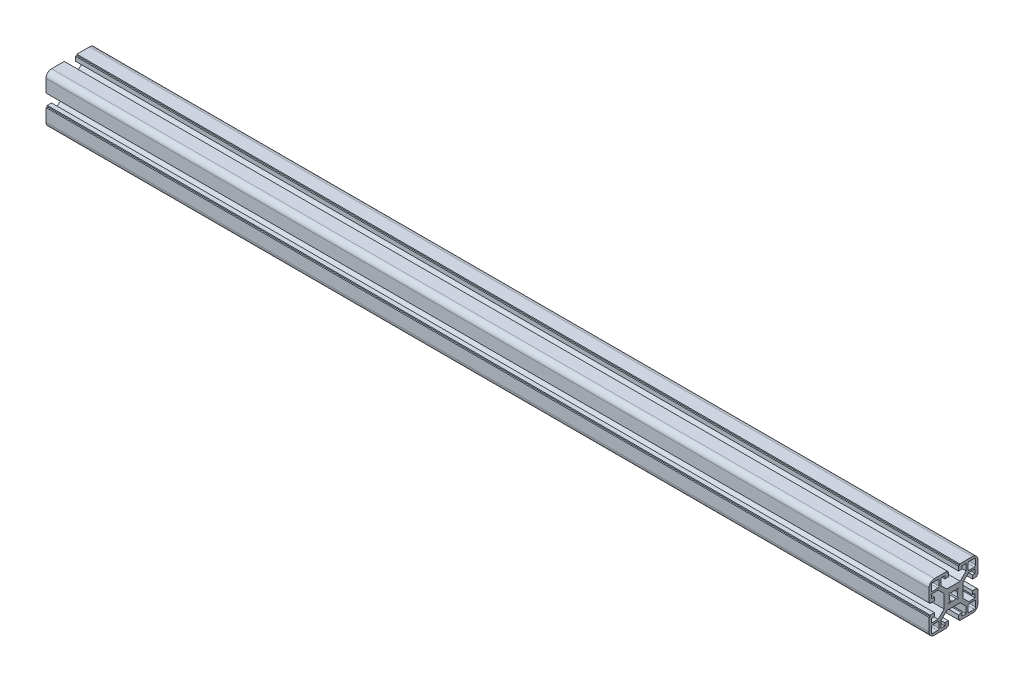
SolidWorks part; units mm, degrees
ref_plane "前视基准面" through (0, 0, 0) normal (0, 0, 1) x (1, 0, 0)
ref_plane "上视基准面" through (0, 0, 0) normal (0, 1, 0) x (1, 0, 0)
ref_plane "右视基准面" through (0, 0, 0) normal (1, 0, 0) x (0, 0, -1)
other "Configuration Table"
sketch "草图1" plane through (0, 0, 0) normal (1, 0, 0) x (0, 0, -1)
  line L0 (4.82, 19.28) -> (3.82, 19.28)
  line L1 (3.82, 19.28) -> (3.82, 15.78)
  line L2 (3.82, 15.78) -> (6.7364, 15.78)
  line L3 (6.7364, 15.78) -> (6.7364, 18.03)
  line L4 (6.7364, 18.03) -> (10.02, 18.03)
  line L5 (10.02, 18.03) -> (10.02, 12.7013)
  line L6 (10.02, 12.7013) -> (5.1987, 7.88)
  line L7 (5.1987, 7.88) -> (-5.7586, 7.88)
  line L8 (-5.7586, 7.88) -> (-10.58, 12.7013)
  line L9 (-10.58, 12.7013) -> (-10.58, 18.03)
  line L10 (-10.58, 18.03) -> (-7.2963, 18.03)
  line L11 (-7.2963, 18.03) -> (-7.2963, 15.78)
  line L12 (-7.2963, 15.78) -> (-4.38, 15.78)
  line L13 (-4.38, 15.78) -> (-4.38, 19.28)
  line L14 (-4.38, 19.28) -> (-5.38, 19.28)
  line L15 (-5.38, 19.28) -> (-5.38, 20.28)
  line L16 (-5.38, 20.28) -> (-15.78, 20.28)
  line L17 (-20.28, 15.78) -> (-20.28, 5.38)
  line L18 (-20.28, 5.38) -> (-19.28, 5.38)
  line L19 (-19.28, 5.38) -> (-19.28, 4.38)
  line L20 (-19.28, 4.38) -> (-15.78, 4.38)
  line L21 (-15.78, 4.38) -> (-15.78, 7.2963)
  line L22 (-15.78, 7.2963) -> (-18.03, 7.2963)
  line L23 (-18.03, 7.2963) -> (-18.03, 10.58)
  line L24 (-18.03, 10.58) -> (-12.7013, 10.58)
  line L25 (-12.7013, 10.58) -> (-7.88, 5.7586)
  line L26 (-7.88, 5.7586) -> (-7.88, -5.1987)
  line L27 (-7.88, -5.1987) -> (-12.7013, -10.02)
  line L28 (-12.7013, -10.02) -> (-18.03, -10.02)
  line L29 (-18.03, -10.02) -> (-18.03, -6.7364)
  line L30 (-18.03, -6.7364) -> (-15.78, -6.7364)
  line L31 (-15.78, -6.7364) -> (-15.78, -3.82)
  line L32 (-15.78, -3.82) -> (-19.28, -3.82)
  line L33 (-19.28, -3.82) -> (-19.28, -4.82)
  line L34 (-19.28, -4.82) -> (-20.28, -4.82)
  line L35 (-20.28, -4.82) -> (-20.28, -15.22)
  line L36 (-15.78, -19.72) -> (-5.38, -19.72)
  line L37 (-5.38, -19.72) -> (-5.38, -18.72)
  line L38 (-5.38, -18.72) -> (-4.38, -18.72)
  line L39 (-4.38, -18.72) -> (-4.38, -15.22)
  line L40 (-4.38, -15.22) -> (-7.2963, -15.22)
  line L41 (-7.2963, -15.22) -> (-7.2963, -17.47)
  line L42 (-7.2963, -17.47) -> (-10.58, -17.47)
  line L43 (-10.58, -17.47) -> (-10.58, -12.1414)
  line L44 (-10.58, -12.1414) -> (-5.7586, -7.32)
  line L45 (-5.7586, -7.32) -> (5.1987, -7.32)
  line L46 (5.1987, -7.32) -> (10.02, -12.1414)
  line L47 (10.02, -12.1414) -> (10.02, -17.47)
  line L48 (10.02, -17.47) -> (6.7364, -17.47)
  line L49 (6.7364, -17.47) -> (6.7364, -15.22)
  line L50 (6.7364, -15.22) -> (3.82, -15.22)
  line L51 (3.82, -15.22) -> (3.82, -18.72)
  line L52 (3.82, -18.72) -> (4.82, -18.72)
  line L53 (4.82, -18.72) -> (4.82, -19.72)
  line L54 (4.82, -19.72) -> (15.22, -19.72)
  line L55 (19.72, -15.22) -> (19.72, -4.82)
  line L56 (19.72, -4.82) -> (18.72, -4.82)
  line L57 (18.72, -4.82) -> (18.72, -3.82)
  line L58 (18.72, -3.82) -> (15.22, -3.82)
  line L59 (15.22, -3.82) -> (15.22, -6.7364)
  line L60 (15.22, -6.7364) -> (17.47, -6.7364)
  line L61 (17.47, -6.7364) -> (17.47, -10.02)
  line L62 (17.47, -10.02) -> (12.1414, -10.02)
  line L63 (12.1414, -10.02) -> (7.32, -5.1987)
  line L64 (7.32, -5.1987) -> (7.32, 5.7586)
  line L65 (7.32, 5.7586) -> (12.1414, 10.58)
  line L66 (12.1414, 10.58) -> (17.47, 10.58)
  line L67 (17.47, 10.58) -> (17.47, 7.2963)
  line L68 (17.47, 7.2963) -> (15.22, 7.2963)
  line L69 (15.22, 7.2963) -> (15.22, 4.38)
  line L70 (15.22, 4.38) -> (18.72, 4.38)
  line L71 (18.72, 4.38) -> (18.72, 5.38)
  line L72 (18.72, 5.38) -> (19.72, 5.38)
  line L73 (19.72, 5.38) -> (19.72, 15.78)
  line L74 (15.22, 20.28) -> (4.82, 20.28)
  line L75 (4.82, 20.28) -> (4.82, 19.28)
  line L76 (-13.08, -17.72) -> (-17.28, -17.72)
  line L77 (-18.28, -16.72) -> (-18.28, -12.52)
  line L78 (-17.28, -11.52) -> (-13.08, -11.52)
  line L79 (-12.08, -12.52) -> (-12.08, -16.72)
  line L80 (-17.28, 18.28) -> (-13.08, 18.28)
  line L81 (-12.08, 17.28) -> (-12.08, 13.08)
  line L82 (-13.08, 12.08) -> (-17.28, 12.08)
  line L83 (-18.28, 13.08) -> (-18.28, 17.28)
  line L84 (16.72, 12.08) -> (12.52, 12.08)
  line L85 (11.52, 13.08) -> (11.52, 17.28)
  line L86 (12.52, 18.28) -> (16.72, 18.28)
  line L87 (17.72, 17.28) -> (17.72, 13.08)
  line L88 (3.7505, -3.0434) -> (3.0434, -3.7505)
  line L89 (3.0434, -3.7505) -> (1.7445, -2.4516)
  line L90 (-2.3044, -2.4516) -> (-3.6033, -3.7505)
  line L91 (-3.6033, -3.7505) -> (-4.3104, -3.0434)
  line L92 (-4.3104, -3.0434) -> (-3.0115, -1.7445)
  line L93 (-3.0115, 2.3044) -> (-4.3104, 3.6033)
  line L94 (-4.3104, 3.6033) -> (-3.6033, 4.3104)
  line L95 (-3.6033, 4.3104) -> (-2.3044, 3.0115)
  line L96 (1.7445, 3.0115) -> (3.0434, 4.3104)
  line L97 (3.0434, 4.3104) -> (3.7505, 3.6033)
  line L98 (3.7505, 3.6033) -> (2.4516, 2.3044)
  line L99 (2.4516, -1.7445) -> (3.7505, -3.0434)
  line L100 (17.72, -12.52) -> (17.72, -16.72)
  line L101 (16.72, -17.72) -> (12.52, -17.72)
  line L102 (11.52, -16.72) -> (11.52, -12.52)
  line L103 (12.52, -11.52) -> (16.72, -11.52)
  arc A0 (-15.78, 20.28) -> (-20.28, 15.78) centre (-15.78, 15.78) ccw
  arc A1 (-20.28, -15.22) -> (-15.78, -19.72) centre (-15.78, -15.22) ccw
  arc A2 (15.22, -19.72) -> (19.72, -15.22) centre (15.22, -15.22) ccw
  arc A3 (19.72, 15.78) -> (15.22, 20.28) centre (15.22, 15.78) ccw
  arc A4 (-12.08, -16.72) -> (-13.08, -17.72) centre (-13.08, -16.72) cw
  arc A5 (-17.28, -17.72) -> (-18.28, -16.72) centre (-17.28, -16.72) cw
  arc A6 (-18.28, -12.52) -> (-17.28, -11.52) centre (-17.28, -12.52) cw
  arc A7 (-13.08, -11.52) -> (-12.08, -12.52) centre (-13.08, -12.52) cw
  arc A8 (-18.28, 17.28) -> (-17.28, 18.28) centre (-17.28, 17.28) cw
  arc A9 (-13.08, 18.28) -> (-12.08, 17.28) centre (-13.08, 17.28) cw
  arc A10 (-12.08, 13.08) -> (-13.08, 12.08) centre (-13.08, 13.08) cw
  arc A11 (-17.28, 12.08) -> (-18.28, 13.08) centre (-17.28, 13.08) cw
  arc A12 (17.72, 13.08) -> (16.72, 12.08) centre (16.72, 13.08) cw
  arc A13 (12.52, 12.08) -> (11.52, 13.08) centre (12.52, 13.08) cw
  arc A14 (11.52, 17.28) -> (12.52, 18.28) centre (12.52, 17.28) cw
  arc A15 (16.72, 18.28) -> (17.72, 17.28) centre (16.72, 17.28) cw
  arc A16 (1.7445, -2.4516) -> (-2.3044, -2.4516) centre (-0.28, 0.28) cw
  arc A17 (-3.0115, -1.7445) -> (-3.0115, 2.3044) centre (-0.28, 0.28) cw
  arc A18 (-2.3044, 3.0115) -> (1.7445, 3.0115) centre (-0.28, 0.28) cw
  arc A19 (2.4516, 2.3044) -> (2.4516, -1.7445) centre (-0.28, 0.28) cw
  arc A20 (16.72, -11.52) -> (17.72, -12.52) centre (16.72, -12.52) cw
  arc A21 (17.72, -16.72) -> (16.72, -17.72) centre (16.72, -16.72) cw
  arc A22 (12.52, -17.72) -> (11.52, -16.72) centre (12.52, -16.72) cw
  arc A23 (11.52, -12.52) -> (12.52, -11.52) centre (12.52, -12.52) cw
extrude "凸台-拉伸1" add sketch "草图1" against normal blind 50
sketch "草图2" plane through (0, 0, 0) normal (1, 0, 0) x (0, 0, -1)
  line L4 (-17.28, -17.72) -> (-13.08, -17.72)
  line L5 (-18.28, -12.52) -> (-18.28, -16.72)
  line L6 (-13.08, -11.52) -> (-17.28, -11.52)
  line L7 (-12.08, -16.72) -> (-12.08, -12.52)
  line L8 (-17.28, -17.72) -> (-13.08, -17.72)
  line L9 (-18.28, -12.52) -> (-18.28, -16.72)
  line L10 (-13.08, -11.52) -> (-17.28, -11.52)
  line L11 (-12.08, -16.72) -> (-12.08, -12.52)
  line L12 (-13.08, 18.28) -> (-17.28, 18.28)
  line L13 (-12.08, 13.08) -> (-12.08, 17.28)
  line L14 (-17.28, 12.08) -> (-13.08, 12.08)
  line L15 (-18.28, 17.28) -> (-18.28, 13.08)
  line L16 (-13.08, 18.28) -> (-17.28, 18.28)
  line L17 (-12.08, 13.08) -> (-12.08, 17.28)
  line L18 (-17.28, 12.08) -> (-13.08, 12.08)
  line L19 (-18.28, 17.28) -> (-18.28, 13.08)
  line L20 (11.52, 17.28) -> (11.52, 13.08)
  line L21 (16.72, 18.28) -> (12.52, 18.28)
  line L22 (17.72, 13.08) -> (17.72, 17.28)
  line L23 (12.52, 12.08) -> (16.72, 12.08)
  line L24 (11.52, 17.28) -> (11.52, 13.08)
  line L25 (16.72, 18.28) -> (12.52, 18.28)
  line L26 (17.72, 13.08) -> (17.72, 17.28)
  line L27 (12.52, 12.08) -> (16.72, 12.08)
  line L28 (11.52, -12.52) -> (11.52, -16.72)
  line L29 (16.72, -11.52) -> (12.52, -11.52)
  line L30 (17.72, -16.72) -> (17.72, -12.52)
  line L31 (12.52, -17.72) -> (16.72, -17.72)
  line L32 (11.52, -12.52) -> (11.52, -16.72)
  line L33 (16.72, -11.52) -> (12.52, -11.52)
  line L34 (17.72, -16.72) -> (17.72, -12.52)
  line L35 (12.52, -17.72) -> (16.72, -17.72)
  line L36 (-4.3104, 3.6033) -> (-3.0115, 2.3044)
  line L37 (-3.6033, 4.3104) -> (-4.3104, 3.6033)
  line L38 (-2.3044, 3.0115) -> (-3.6033, 4.3104)
  line L39 (3.0434, 4.3104) -> (1.7445, 3.0115)
  line L40 (3.7505, 3.6033) -> (3.0434, 4.3104)
  line L41 (2.4516, 2.3044) -> (3.7505, 3.6033)
  line L42 (3.7505, -3.0434) -> (2.4516, -1.7445)
  line L43 (3.0434, -3.7505) -> (3.7505, -3.0434)
  line L44 (1.7445, -2.4516) -> (3.0434, -3.7505)
  line L45 (-3.6033, -3.7505) -> (-2.3044, -2.4516)
  line L46 (-4.3104, -3.0434) -> (-3.6033, -3.7505)
  line L47 (-3.0115, -1.7445) -> (-4.3104, -3.0434)
  line L48 (-4.3104, 3.6033) -> (-3.0115, 2.3044)
  line L49 (-3.6033, 4.3104) -> (-4.3104, 3.6033)
  line L50 (-2.3044, 3.0115) -> (-3.6033, 4.3104)
  line L51 (3.0434, 4.3104) -> (1.7445, 3.0115)
  line L52 (3.7505, 3.6033) -> (3.0434, 4.3104)
  line L53 (2.4516, 2.3044) -> (3.7505, 3.6033)
  line L54 (3.7505, -3.0434) -> (2.4516, -1.7445)
  line L55 (3.0434, -3.7505) -> (3.7505, -3.0434)
  line L56 (1.7445, -2.4516) -> (3.0434, -3.7505)
  line L57 (-3.6033, -3.7505) -> (-2.3044, -2.4516)
  line L58 (-4.3104, -3.0434) -> (-3.6033, -3.7505)
  line L59 (-3.0115, -1.7445) -> (-4.3104, -3.0434)
  line L84 (19.72, 5.38) -> (19.72, 15.78)
  line L85 (18.72, 5.38) -> (19.72, 5.38)
  line L86 (18.72, 4.38) -> (18.72, 5.38)
  line L87 (15.22, 4.38) -> (18.72, 4.38)
  line L88 (15.22, 7.2963) -> (15.22, 4.38)
  line L89 (17.47, 7.2963) -> (15.22, 7.2963)
  line L90 (17.47, 10.58) -> (17.47, 7.2963)
  line L91 (12.1414, 10.58) -> (17.47, 10.58)
  line L92 (7.32, 5.7586) -> (12.1414, 10.58)
  line L93 (7.32, -5.1987) -> (7.32, 5.7586)
  line L94 (12.1414, -10.02) -> (7.32, -5.1987)
  line L95 (17.47, -10.02) -> (12.1414, -10.02)
  line L96 (17.47, -6.7364) -> (17.47, -10.02)
  line L97 (15.22, -6.7364) -> (17.47, -6.7364)
  line L98 (15.22, -3.82) -> (15.22, -6.7364)
  line L99 (18.72, -3.82) -> (15.22, -3.82)
  line L100 (18.72, -4.82) -> (18.72, -3.82)
  line L101 (19.72, -4.82) -> (18.72, -4.82)
  line L102 (19.72, -15.22) -> (19.72, -4.82)
  line L103 (4.82, -19.72) -> (15.22, -19.72)
  line L104 (4.82, -18.72) -> (4.82, -19.72)
  line L105 (3.82, -18.72) -> (4.82, -18.72)
  line L106 (3.82, -15.22) -> (3.82, -18.72)
  line L107 (6.7364, -15.22) -> (3.82, -15.22)
  line L108 (6.7364, -17.47) -> (6.7364, -15.22)
  line L109 (10.02, -17.47) -> (6.7364, -17.47)
  line L110 (10.02, -12.1414) -> (10.02, -17.47)
  line L111 (5.1987, -7.32) -> (10.02, -12.1414)
  line L112 (-5.7586, -7.32) -> (5.1987, -7.32)
  line L113 (-10.58, -12.1414) -> (-5.7586, -7.32)
  line L114 (-10.58, -17.47) -> (-10.58, -12.1414)
  line L115 (-7.2963, -17.47) -> (-10.58, -17.47)
  line L116 (-7.2963, -15.22) -> (-7.2963, -17.47)
  line L117 (-4.38, -15.22) -> (-7.2963, -15.22)
  line L118 (-4.38, -18.72) -> (-4.38, -15.22)
  line L119 (-5.38, -18.72) -> (-4.38, -18.72)
  line L120 (-5.38, -19.72) -> (-5.38, -18.72)
  line L121 (-15.78, -19.72) -> (-5.38, -19.72)
  line L122 (-20.28, -4.82) -> (-20.28, -15.22)
  line L123 (-19.28, -4.82) -> (-20.28, -4.82)
  line L124 (-19.28, -3.82) -> (-19.28, -4.82)
  line L125 (-15.78, -3.82) -> (-19.28, -3.82)
  line L126 (-15.78, -6.7364) -> (-15.78, -3.82)
  line L127 (-18.03, -6.7364) -> (-15.78, -6.7364)
  line L128 (-18.03, -10.02) -> (-18.03, -6.7364)
  line L129 (-12.7013, -10.02) -> (-18.03, -10.02)
  line L130 (-7.88, -5.1987) -> (-12.7013, -10.02)
  line L131 (-7.88, 5.7586) -> (-7.88, -5.1987)
  line L132 (-12.7013, 10.58) -> (-7.88, 5.7586)
  line L133 (-18.03, 10.58) -> (-12.7013, 10.58)
  line L134 (-18.03, 7.2963) -> (-18.03, 10.58)
  line L135 (-15.78, 7.2963) -> (-18.03, 7.2963)
  line L136 (-15.78, 4.38) -> (-15.78, 7.2963)
  line L137 (-19.28, 4.38) -> (-15.78, 4.38)
  line L138 (-19.28, 5.38) -> (-19.28, 4.38)
  line L139 (-20.28, 5.38) -> (-19.28, 5.38)
  line L140 (-20.28, 15.78) -> (-20.28, 5.38)
  line L141 (-5.38, 20.28) -> (-15.78, 20.28)
  line L142 (-5.38, 19.28) -> (-5.38, 20.28)
  line L143 (-4.38, 19.28) -> (-5.38, 19.28)
  line L144 (-4.38, 15.78) -> (-4.38, 19.28)
  line L145 (-7.2963, 15.78) -> (-4.38, 15.78)
  line L146 (-7.2963, 18.03) -> (-7.2963, 15.78)
  line L147 (-10.58, 18.03) -> (-7.2963, 18.03)
  line L148 (-10.58, 12.7013) -> (-10.58, 18.03)
  line L149 (-5.7586, 7.88) -> (-10.58, 12.7013)
  line L150 (5.1987, 7.88) -> (-5.7586, 7.88)
  line L151 (10.02, 12.7013) -> (5.1987, 7.88)
  line L152 (10.02, 18.03) -> (10.02, 12.7013)
  line L153 (6.7364, 18.03) -> (10.02, 18.03)
  line L154 (6.7364, 15.78) -> (6.7364, 18.03)
  line L155 (3.82, 15.78) -> (6.7364, 15.78)
  line L156 (3.82, 19.28) -> (3.82, 15.78)
  line L157 (4.82, 19.28) -> (3.82, 19.28)
  line L158 (4.82, 20.28) -> (4.82, 19.28)
  line L159 (15.22, 20.28) -> (4.82, 20.28)
  line L160 (19.72, 5.38) -> (19.72, 15.78)
  line L161 (18.72, 5.38) -> (19.72, 5.38)
  line L162 (18.72, 4.38) -> (18.72, 5.38)
  line L163 (15.22, 4.38) -> (18.72, 4.38)
  line L164 (15.22, 7.2963) -> (15.22, 4.38)
  line L165 (17.47, 7.2963) -> (15.22, 7.2963)
  line L166 (17.47, 10.58) -> (17.47, 7.2963)
  line L167 (12.1414, 10.58) -> (17.47, 10.58)
  line L168 (7.32, 5.7586) -> (12.1414, 10.58)
  line L169 (7.32, -5.1987) -> (7.32, 5.7586)
  line L170 (12.1414, -10.02) -> (7.32, -5.1987)
  line L171 (17.47, -10.02) -> (12.1414, -10.02)
  line L172 (17.47, -6.7364) -> (17.47, -10.02)
  line L173 (15.22, -6.7364) -> (17.47, -6.7364)
  line L174 (15.22, -3.82) -> (15.22, -6.7364)
  line L175 (18.72, -3.82) -> (15.22, -3.82)
  line L176 (18.72, -4.82) -> (18.72, -3.82)
  line L177 (19.72, -4.82) -> (18.72, -4.82)
  line L178 (19.72, -15.22) -> (19.72, -4.82)
  line L179 (4.82, -19.72) -> (15.22, -19.72)
  line L180 (4.82, -18.72) -> (4.82, -19.72)
  line L181 (3.82, -18.72) -> (4.82, -18.72)
  line L182 (3.82, -15.22) -> (3.82, -18.72)
  line L183 (6.7364, -15.22) -> (3.82, -15.22)
  line L184 (6.7364, -17.47) -> (6.7364, -15.22)
  line L185 (10.02, -17.47) -> (6.7364, -17.47)
  line L186 (10.02, -12.1414) -> (10.02, -17.47)
  line L187 (5.1987, -7.32) -> (10.02, -12.1414)
  line L188 (-5.7586, -7.32) -> (5.1987, -7.32)
  line L189 (-10.58, -12.1414) -> (-5.7586, -7.32)
  line L190 (-10.58, -17.47) -> (-10.58, -12.1414)
  line L191 (-7.2963, -17.47) -> (-10.58, -17.47)
  line L192 (-7.2963, -15.22) -> (-7.2963, -17.47)
  line L193 (-4.38, -15.22) -> (-7.2963, -15.22)
  line L194 (-4.38, -18.72) -> (-4.38, -15.22)
  line L195 (-5.38, -18.72) -> (-4.38, -18.72)
  line L196 (-5.38, -19.72) -> (-5.38, -18.72)
  line L197 (-15.78, -19.72) -> (-5.38, -19.72)
  line L198 (-20.28, -4.82) -> (-20.28, -15.22)
  line L199 (-19.28, -4.82) -> (-20.28, -4.82)
  line L200 (-19.28, -3.82) -> (-19.28, -4.82)
  line L201 (-15.78, -3.82) -> (-19.28, -3.82)
  line L202 (-15.78, -6.7364) -> (-15.78, -3.82)
  line L203 (-18.03, -6.7364) -> (-15.78, -6.7364)
  line L204 (-18.03, -10.02) -> (-18.03, -6.7364)
  line L205 (-12.7013, -10.02) -> (-18.03, -10.02)
  line L206 (-7.88, -5.1987) -> (-12.7013, -10.02)
  line L207 (-7.88, 5.7586) -> (-7.88, -5.1987)
  line L208 (-12.7013, 10.58) -> (-7.88, 5.7586)
  line L209 (-18.03, 10.58) -> (-12.7013, 10.58)
  line L210 (-18.03, 7.2963) -> (-18.03, 10.58)
  line L211 (-15.78, 7.2963) -> (-18.03, 7.2963)
  line L212 (-15.78, 4.38) -> (-15.78, 7.2963)
  line L213 (-19.28, 4.38) -> (-15.78, 4.38)
  line L214 (-19.28, 5.38) -> (-19.28, 4.38)
  line L215 (-20.28, 5.38) -> (-19.28, 5.38)
  line L216 (-20.28, 15.78) -> (-20.28, 5.38)
  line L217 (-5.38, 20.28) -> (-15.78, 20.28)
  line L218 (-5.38, 19.28) -> (-5.38, 20.28)
  line L219 (-4.38, 19.28) -> (-5.38, 19.28)
  line L220 (-4.38, 15.78) -> (-4.38, 19.28)
  line L221 (-7.2963, 15.78) -> (-4.38, 15.78)
  line L222 (-7.2963, 18.03) -> (-7.2963, 15.78)
  line L223 (-10.58, 18.03) -> (-7.2963, 18.03)
  line L224 (-10.58, 12.7013) -> (-10.58, 18.03)
  line L225 (-5.7586, 7.88) -> (-10.58, 12.7013)
  line L226 (5.1987, 7.88) -> (-5.7586, 7.88)
  line L227 (10.02, 12.7013) -> (5.1987, 7.88)
  line L228 (10.02, 18.03) -> (10.02, 12.7013)
  line L229 (6.7364, 18.03) -> (10.02, 18.03)
  line L230 (6.7364, 15.78) -> (6.7364, 18.03)
  line L231 (3.82, 15.78) -> (6.7364, 15.78)
  line L232 (3.82, 19.28) -> (3.82, 15.78)
  line L233 (4.82, 19.28) -> (3.82, 19.28)
  line L234 (4.82, 20.28) -> (4.82, 19.28)
  line L235 (15.22, 20.28) -> (4.82, 20.28)
  arc A4 (-18.28, -16.72) -> (-17.28, -17.72) centre (-17.28, -16.72) ccw
  arc A5 (-17.28, -11.52) -> (-18.28, -12.52) centre (-17.28, -12.52) ccw
  arc A6 (-12.08, -12.52) -> (-13.08, -11.52) centre (-13.08, -12.52) ccw
  arc A7 (-13.08, -17.72) -> (-12.08, -16.72) centre (-13.08, -16.72) ccw
  arc A8 (-18.28, -16.72) -> (-17.28, -17.72) centre (-17.28, -16.72) ccw
  arc A9 (-17.28, -11.52) -> (-18.28, -12.52) centre (-17.28, -12.52) ccw
  arc A10 (-12.08, -12.52) -> (-13.08, -11.52) centre (-13.08, -12.52) ccw
  arc A11 (-13.08, -17.72) -> (-12.08, -16.72) centre (-13.08, -16.72) ccw
  arc A12 (15.22, -19.72) -> (19.72, -15.22) centre (15.22, -15.22) ccw
  arc A13 (-20.28, -15.22) -> (-15.78, -19.72) centre (-15.78, -15.22) ccw
  arc A14 (-15.78, 20.28) -> (-20.28, 15.78) centre (-15.78, 15.78) ccw
  arc A15 (19.72, 15.78) -> (15.22, 20.28) centre (15.22, 15.78) ccw
  arc A16 (15.22, -19.72) -> (19.72, -15.22) centre (15.22, -15.22) ccw
  arc A17 (-20.28, -15.22) -> (-15.78, -19.72) centre (-15.78, -15.22) ccw
  arc A18 (-15.78, 20.28) -> (-20.28, 15.78) centre (-15.78, 15.78) ccw
  arc A19 (19.72, 15.78) -> (15.22, 20.28) centre (15.22, 15.78) ccw
  arc A20 (-12.08, 17.28) -> (-13.08, 18.28) centre (-13.08, 17.28) ccw
  arc A21 (-13.08, 12.08) -> (-12.08, 13.08) centre (-13.08, 13.08) ccw
  arc A22 (-18.28, 13.08) -> (-17.28, 12.08) centre (-17.28, 13.08) ccw
  arc A23 (-17.28, 18.28) -> (-18.28, 17.28) centre (-17.28, 17.28) ccw
  arc A24 (-12.08, 17.28) -> (-13.08, 18.28) centre (-13.08, 17.28) ccw
  arc A25 (-13.08, 12.08) -> (-12.08, 13.08) centre (-13.08, 13.08) ccw
  arc A26 (-18.28, 13.08) -> (-17.28, 12.08) centre (-17.28, 13.08) ccw
  arc A27 (-17.28, 18.28) -> (-18.28, 17.28) centre (-17.28, 17.28) ccw
  arc A28 (12.52, 18.28) -> (11.52, 17.28) centre (12.52, 17.28) ccw
  arc A29 (17.72, 17.28) -> (16.72, 18.28) centre (16.72, 17.28) ccw
  arc A30 (16.72, 12.08) -> (17.72, 13.08) centre (16.72, 13.08) ccw
  arc A31 (11.52, 13.08) -> (12.52, 12.08) centre (12.52, 13.08) ccw
  arc A32 (12.52, 18.28) -> (11.52, 17.28) centre (12.52, 17.28) ccw
  arc A33 (17.72, 17.28) -> (16.72, 18.28) centre (16.72, 17.28) ccw
  arc A34 (16.72, 12.08) -> (17.72, 13.08) centre (16.72, 13.08) ccw
  arc A35 (11.52, 13.08) -> (12.52, 12.08) centre (12.52, 13.08) ccw
  arc A36 (1.7445, 3.0115) -> (-2.3044, 3.0115) centre (-0.28, 0.28) ccw
  arc A37 (2.4516, -1.7445) -> (2.4516, 2.3044) centre (-0.28, 0.28) ccw
  arc A38 (-2.3044, -2.4516) -> (1.7445, -2.4516) centre (-0.28, 0.28) ccw
  arc A39 (-3.0115, 2.3044) -> (-3.0115, -1.7445) centre (-0.28, 0.28) ccw
  arc A40 (1.7445, 3.0115) -> (-2.3044, 3.0115) centre (-0.28, 0.28) ccw
  arc A41 (2.4516, -1.7445) -> (2.4516, 2.3044) centre (-0.28, 0.28) ccw
  arc A42 (-2.3044, -2.4516) -> (1.7445, -2.4516) centre (-0.28, 0.28) ccw
  arc A43 (-3.0115, 2.3044) -> (-3.0115, -1.7445) centre (-0.28, 0.28) ccw
  arc A44 (12.52, -11.52) -> (11.52, -12.52) centre (12.52, -12.52) ccw
  arc A45 (17.72, -12.52) -> (16.72, -11.52) centre (16.72, -12.52) ccw
  arc A46 (16.72, -17.72) -> (17.72, -16.72) centre (16.72, -16.72) ccw
  arc A47 (11.52, -16.72) -> (12.52, -17.72) centre (12.52, -16.72) ccw
  arc A48 (12.52, -11.52) -> (11.52, -12.52) centre (12.52, -12.52) ccw
  arc A49 (17.72, -12.52) -> (16.72, -11.52) centre (16.72, -12.52) ccw
  arc A50 (16.72, -17.72) -> (17.72, -16.72) centre (16.72, -16.72) ccw
  arc A51 (11.52, -16.72) -> (12.52, -17.72) centre (12.52, -16.72) ccw
  dimension "D1" = 0
  dimension "D2" = 0
  dimension "D3" = 0
  dimension "D4" = 0
  dimension "D5" = 0
  dimension "D6" = 0
extrude "凸台-拉伸2" add sketch "草图2" against normal blind 720
sketch "草图4" plane through (0, 0, 0) normal (0, 1, 0) x (1, 0, 0)
  line L0 (-720, 4.82) -> (-720, -5.38) construction
  line L1 (-1720, -0.28) -> (48280, -0.28) construction
  line L2 (-360, -1000.28) -> (-360, 48999.72) construction
  line L3 (-382.5, -0.28) -> (-337.5, -0.28) construction
  line L4 (-400, -0.28) -> (-320, -0.28) construction
  circle A0 centre (-382.5, -0.28) radius 3
  circle A1 centre (-337.5, -0.28) radius 3
  circle A2 centre (-320, -0.28) radius 3
  circle A3 centre (-400, -0.28) radius 3
  point P7 (-720, -0.28)
  point P12 (-360, -0.28)
  point P17 (-360, -0.28)
  dimension "D3" = 6
  dimension "D4" = 6
  dimension "D6" = 6
  dimension "D7" = 6
  dimension "D1" = 360
  dimension "D2" = 45
  dimension "D5" = 80
extrude "切除-拉伸1" cut sketch "草图4" against normal up to surface (40 mm away) from surface at 20.28 up to face at (-360, -19.72, -10.02) starting at face at (-360, 20.28, -10.02)
